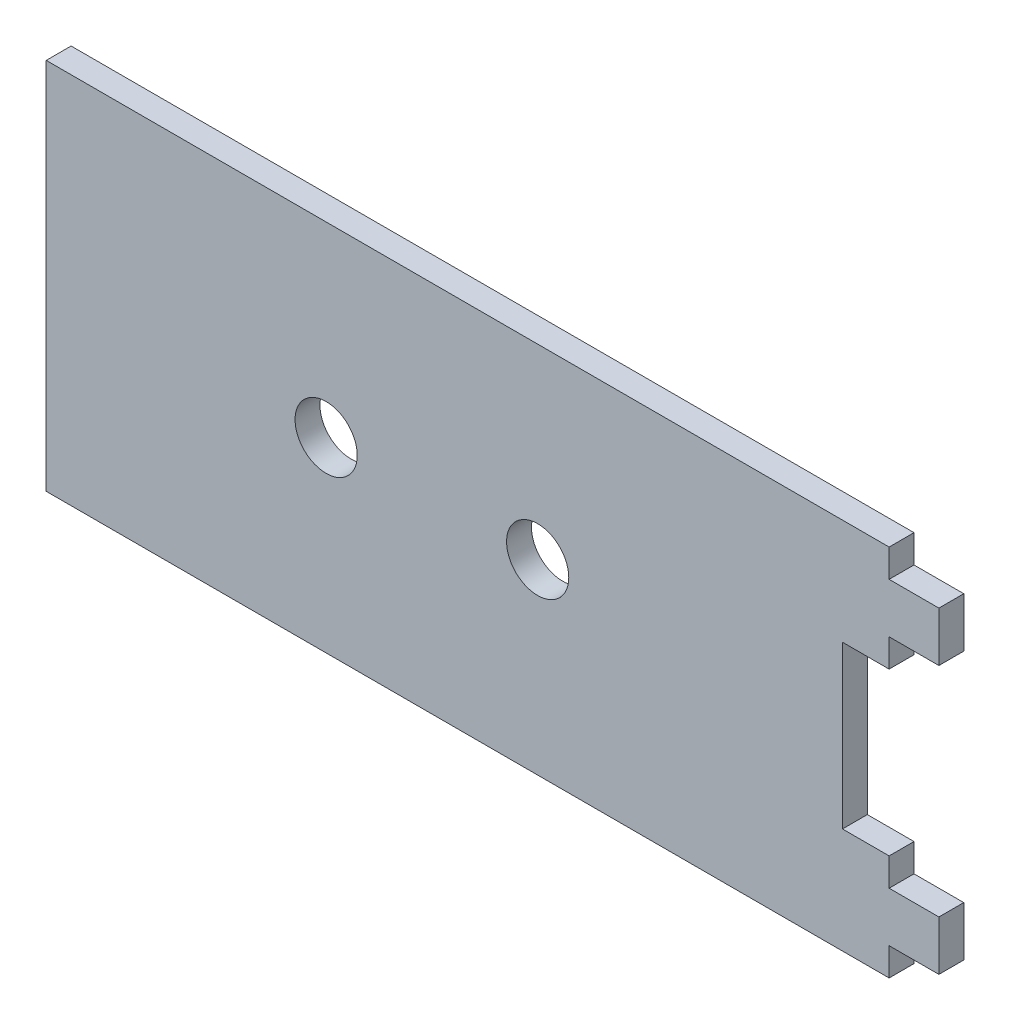
SolidWorks part; units mm, degrees
ref_plane "Front Plane" through (0, 0, 0) normal (0, 0, 1) x (1, 0, 0)
ref_plane "Top Plane" through (0, 0, 0) normal (0, 1, 0) x (1, 0, 0)
ref_plane "Right Plane" through (0, 0, 0) normal (1, 0, 0) x (0, 0, -1)
sketch "Sketch1" plane through (0, 0, 0) normal (0, 0, 1) x (1, 0, 0)
  line L0 (49, 30) -> (56.5, 30)
  line L1 (-79, -30) -> (49, -30)
  line L2 (-79, -30) -> (-79, 30)
  line L3 (-79, 30) -> (49, 30)
  line L6 (56.5, 13) -> (49, 13)
  line L7 (49, 13) -> (49, -13)
  line L8 (49, -13) -> (56.5, -13)
  line L10 (56.5, -30) -> (49, -30)
  line L11 (56.5, 30) -> (56.5, 13) construction
  line L12 (56.5, -13) -> (56.5, -30) construction
  line L13 (56.5, 30) -> (56.5, 25.5)
  line L14 (56.5, 25.5) -> (64.5, 25.5)
  line L15 (64.5, 25.5) -> (64.5, 17.5)
  line L16 (64.5, 17.5) -> (56.5, 17.5)
  line L17 (56.5, 17.5) -> (56.5, 13)
  line L18 (56.5, -13) -> (56.5, -17.5)
  line L19 (56.5, -17.5) -> (64.5, -17.5)
  line L20 (64.5, -17.5) -> (64.5, -25.5)
  line L21 (64.5, -25.5) -> (56.5, -25.5)
  line L22 (56.5, -25.5) -> (56.5, -30)
  circle A0 centre (0, 0) radius 5
  circle A3 centre (-34, 0) radius 5
  point P1 (0, 0)
  point P8 (-79, 0)
  dimension "D3" = 128
  dimension "D4" = 0
  dimension "D5" = 10
  dimension "D1" = 45
  dimension "D7" = 0
  dimension "D2" = 60
  dimension "D6" = 34
  dimension "D8" = 26
  dimension "D9" = 17
  dimension "D10" = 7.5
  dimension "D11" = 8
  dimension "D12" = 8
extrude "Boss-Extrude1" add sketch "Sketch1" along normal blind 4
